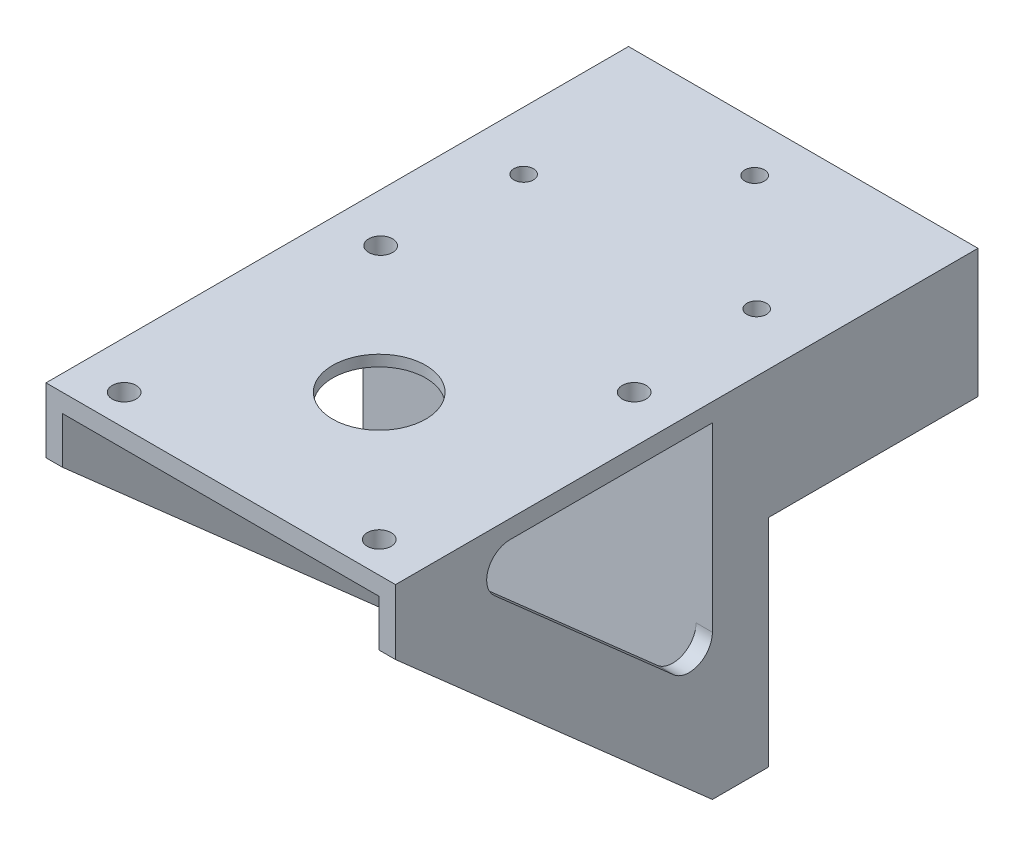
SolidWorks part; units mm, degrees
ref_plane "Front Plane" through (0, 0, 0) normal (0, 0, 1) x (1, 0, 0)
ref_plane "Top Plane" through (0, 0, 0) normal (0, 1, 0) x (1, 0, 0)
ref_plane "Right Plane" through (0, 0, 0) normal (1, 0, 0) x (0, 0, -1)
sketch "Sketch1" plane through (0, 0, 0) normal (0, 1, 0) x (1, 0, 0)
  line L1 (-47.625, 47.625) -> (47.625, 47.625)
  line L2 (-47.625, 47.625) -> (-47.625, -47.625)
  line L3 (-47.625, -47.625) -> (47.625, -47.625)
  line L4 (47.625, 47.625) -> (47.625, -47.625)
  line L5 (-47.625, 47.625) -> (47.625, -47.625) construction
  line L6 (-47.625, -47.625) -> (47.625, 47.625) construction
  line L7 (-47.625, 47.625) -> (47.625, 47.625)
  line L8 (-47.625, 47.625) -> (-47.625, 111.125)
  line L9 (-47.625, 111.125) -> (47.625, 111.125)
  line L10 (47.625, 47.625) -> (47.625, 111.125)
  line L11 (-47.625, 47.625) -> (47.625, 111.125) construction
  line L12 (-47.625, 111.125) -> (47.625, 47.625) construction
  point P0 (0, 0)
  point P8 (0, 79.375)
  dimension "D1" = 95.25
  dimension "D2" = 63.5
extrude "Boss-Extrude1" add sketch "Sketch1" along normal blind 5 contours L1 L10 L9 L8 | L4 L1 L2 L3
sketch "Sketch2" plane through (0, 0, 0) normal (0, -1, 0) x (-1, 0, 0)
  line L0 (47.625, -47.625) -> (-47.625, -47.625) construction
  line L1 (43.18, -47.625) -> (-43.18, -47.625)
  line L2 (43.18, -47.625) -> (43.18, 38.735)
  line L3 (43.18, 38.735) -> (-43.18, 38.735)
  line L4 (-43.18, -47.625) -> (-43.18, 38.735)
  line L5 (43.18, -47.625) -> (-43.18, 38.735) construction
  line L6 (43.18, 38.735) -> (-43.18, -47.625) construction
  line L7 (-43.18, -4.445) -> (-47.625, -4.445) construction
  line L8 (43.18, -4.445) -> (47.625, -4.445) construction
  line L9 (-47.625, 53.975) -> (47.625, 53.975)
  line L11 (47.625, -47.625) -> (47.625, 111.125)
  line L12 (47.625, 111.125) -> (-47.625, 111.125)
  line L13 (-47.625, 111.125) -> (-47.625, -47.625)
  line L14 (-47.625, -47.625) -> (47.625, -47.625)
  line L15 (47.625, -47.625) -> (47.625, 111.125)
  line L16 (47.625, 111.125) -> (-47.625, 111.125)
  line L17 (-47.625, 111.125) -> (-47.625, -47.625)
  line L18 (-47.625, -47.625) -> (47.625, -47.625)
  point P4 (0, -4.445)
  line M5 (47.625, -47.625) -> (47.625, 111.125)
  line M7 (-47.625, 111.125) -> (-47.625, -47.625)
  line M8 (-47.625, -47.625) -> (47.625, -47.625)
  dimension "D1" = 86.36
  dimension "D3" = 57.15
  dimension "D2" = 0
extrude "Boss-Extrude2" add sketch "Sketch2" along normal blind 88.9 contours L9 L4 L3 L2 M7 M8 M5
sketch "Sketch3" plane through (43.18, 0, 0) normal (-1, 0, 0) x (0, 0, 1)
  line L0 (-38.735, -88.9) -> (47.625, -12.7)
  line L1 (47.625, -88.9) -> (47.625, 0) construction
  line L2 (47.625, -12.7) -> (47.625, -88.9)
  line L3 (47.625, -88.9) -> (-38.735, -88.9)
  line L4 (47.625, 0) -> (-38.735, 0) construction
  dimension "D1" = 12.7
extrude "Cut-Extrude1" cut sketch "Sketch3" against normal up to next and the other way up to next
sketch "Sketch4" plane through (0, 0, 0) normal (0, -1, 0) x (-1, 0, 0)
  line L0 (-43.18, 38.735) -> (43.18, -47.625) construction
  circle A0 centre (0, -4.445) radius 37.5
  dimension "D1" = 75
extrude "Cut-Extrude2" cut sketch "Sketch4" against normal blind 2
sketch "Sketch5" plane through (-43.18, 0, 0) normal (1, 0, 0) x (0, 0, -1)
  line L0 (-35.0211, 1.5844) -> (51.3389, -74.6156)
  line L8 (-47.625, 0) -> (-47.625, -12.7)
  line L9 (-47.625, -12.7) -> (38.735, -88.9)
  line L10 (38.735, -88.9) -> (38.735, 0)
  line L11 (38.735, 0) -> (-47.625, 0)
  line L16 (-47.625, 0) -> (-47.625, -12.7)
  line L17 (-47.625, -12.7) -> (38.735, -88.9)
  line L18 (38.735, -88.9) -> (38.735, 0)
  line L19 (38.735, 0) -> (-47.625, 0)
  line M11 (38.735, -88.9) -> (38.735, 0)
  line M12 (38.735, 0) -> (-47.625, 0)
  dimension "D1" = 0
  dimension "D2" = 19.05
extrude "Cut-Extrude3" cut sketch "Sketch5" against normal up to next and the other way up to next contours L0 M12 M11
fillet "Fillet1" radius 6.35 4 edges at (45.4025, -63.4945, -38.735) (45.4025, 0, 33.2254) (-45.4025, 0, 33.2254) (-45.4025, -63.4945, -38.735)
sketch "Sketch6" plane through (0, 0, 0) normal (0, -1, 0) x (1, 0, 0)
  line L4 (47.625, -111.125) -> (47.625, -53.975)
  line L5 (47.625, -53.975) -> (-47.625, -53.975)
  line L6 (-47.625, -53.975) -> (-47.625, -111.125)
  line L7 (-47.625, -111.125) -> (47.625, -111.125)
  line L8 (47.625, -111.125) -> (47.625, -53.975)
  line L9 (47.625, -53.975) -> (-47.625, -53.975)
  line L10 (-47.625, -53.975) -> (-47.625, -111.125)
  line L11 (-47.625, -111.125) -> (47.625, -111.125)
  dimension "D1" = 0
extrude "Boss-Extrude3" add sketch "Sketch6" along normal blind 30
sketch "Sketch7" plane through (0, -30, 0) normal (0, -1, 0) x (-1, 0, 0)
  line L0 (31.75, 53.975) -> (31.75, 111.125) construction
  line L1 (-47.625, 53.975) -> (47.625, 53.975) construction
  line L2 (47.625, 111.125) -> (-47.625, 111.125) construction
  line L3 (0, 53.975) -> (0, 111.125) construction
  line L4 (-31.75, 53.975) -> (-31.75, 111.125) construction
  line L5 (0, 82.55) -> (31.75, 82.55) construction
  line L6 (0, 82.55) -> (-31.75, 82.55) construction
  line L7 (31.75, 66.675) -> (-31.75, 66.675) construction
  circle A0 centre (0, 97.8729) radius 2.665
  circle A1 centre (31.75, 66.675) radius 2.665
  circle A2 centre (-31.75, 66.675) radius 2.665
  dimension "D2" = 12.7
  dimension "D3" = 5.33
  dimension "D1" = 31.75
extrude "Cut-Extrude4" cut sketch "Sketch7" against normal up to next
sketch "Sketch8" plane through (0, 5, 0) normal (0, 1, 0) x (1, 0, 0)
  circle A0 centre (0, -4.445) radius 12.7
  dimension "D1" = 25.4
extrude "Cut-Extrude5" cut sketch "Sketch8" against normal up to next
sketch "Sketch9" plane through (0, 0, 0) normal (0, -1, 0) x (-1, 0, 0)
  circle A0 centre (34.75, -39.195) radius 3.25
  circle A1 centre (-34.75, -39.195) radius 3.25
  circle A2 centre (34.3966, 30.347) radius 3.25
  circle A3 centre (-34.75, 30.305) radius 3.25
  dimension "D1" = 6.5
extrude "Cut-Extrude6" cut sketch "Sketch9" against normal up to next
